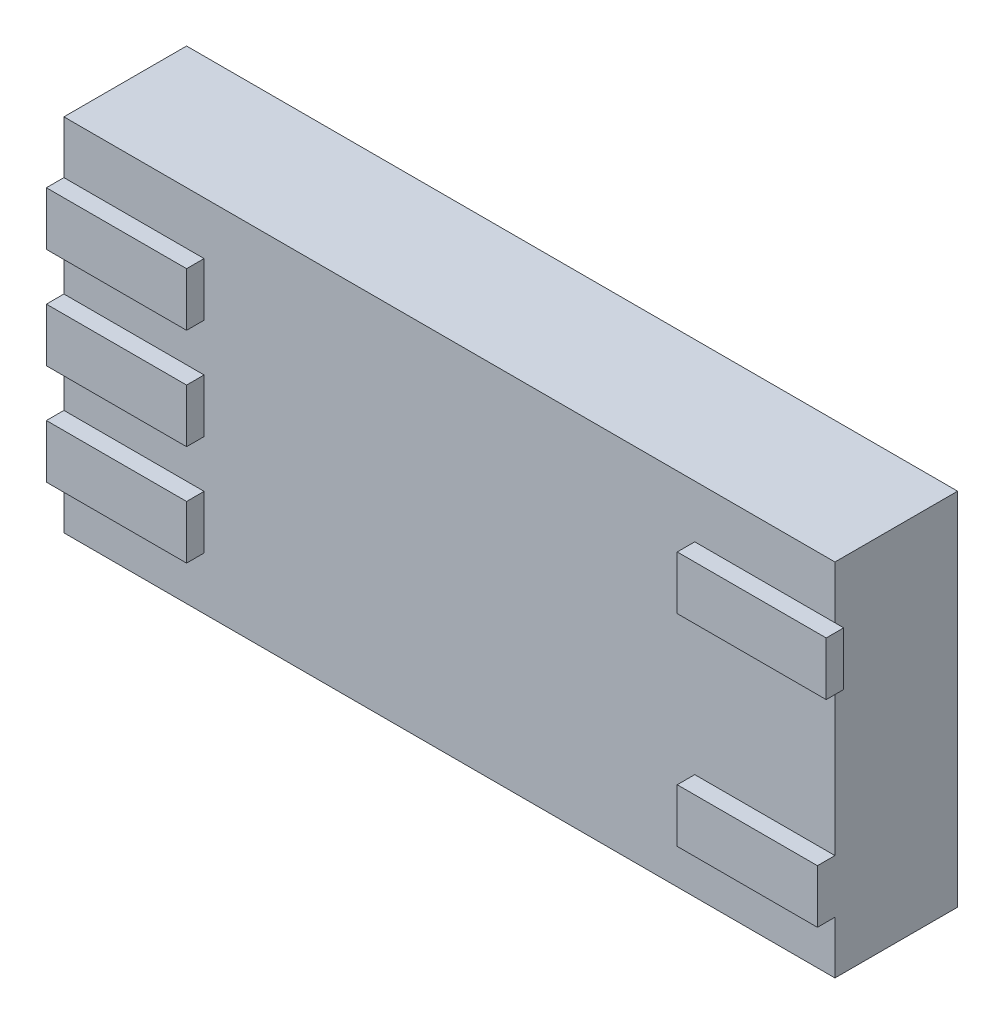
SolidWorks part; units mm, degrees
ref_plane "Front Plane" through (0, 0, 0) normal (0, 0, 1) x (1, 0, 0)
ref_plane "Top Plane" through (0, 0, 0) normal (0, 1, 0) x (1, 0, 0)
ref_plane "Right Plane" through (0, 0, 0) normal (1, 0, 0) x (0, 0, -1)
sketch "Sketch1" plane through (0, 0, 0) normal (0, 0, 1) x (1, 0, 0)
  line L1 (0, 26.1112) -> (55.88, 26.1112)
  line L2 (0, 26.1112) -> (0, 0)
  line L3 (0, 0) -> (55.88, 0)
  line L4 (55.88, 26.1112) -> (55.88, 0)
  dimension "D1" = 55.88
  dimension "D2" = 26.1112
extrude "Boss-Extrude1" add sketch "Sketch1" along normal blind 8.89
sketch "Sketch2" plane through (0, 0, 8.89) normal (0, 0, 1) x (1, 0, 0)
  line L0 (0, 7.6852) -> (10.16, 7.6852)
  line L1 (0, 14.9905) -> (10.16, 14.9905)
  line L2 (0, 14.9905) -> (0, 11.1207)
  line L3 (0, 11.1207) -> (10.16, 11.1207)
  line L4 (10.16, 14.9905) -> (10.16, 11.1207)
  line L5 (0, 7.6852) -> (0, 3.8153)
  line L6 (0, 3.8153) -> (10.16, 3.8153)
  line L7 (10.16, 7.6852) -> (10.16, 3.8153)
  line L8 (0, 22.2959) -> (10.16, 22.2959)
  line L9 (0, 22.2959) -> (0, 18.426)
  line L10 (0, 18.426) -> (10.16, 18.426)
  line L11 (10.16, 22.2959) -> (10.16, 18.426)
  line L12 (45.72, 7.6852) -> (55.88, 7.6852)
  line L13 (45.72, 7.6852) -> (45.72, 3.8153)
  line L14 (45.72, 3.8153) -> (55.88, 3.8153)
  line L15 (55.88, 7.6852) -> (55.88, 3.8153)
  line L16 (55.88, 0) -> (55.88, 26.1112) construction
  line L17 (45.72, 22.2959) -> (55.88, 22.2959)
  line L18 (45.72, 22.2959) -> (45.72, 18.426)
  line L19 (45.72, 18.426) -> (55.88, 18.426)
  line L20 (55.88, 22.2959) -> (55.88, 18.426)
  line L21 (5.08, 26.1112) -> (5.08, 22.2959) construction
  line L22 (5.08, 18.426) -> (5.08, 14.9905) construction
  line L23 (55.88, 26.1112) -> (0, 26.1112) construction
  line L24 (5.08, 3.8153) -> (5.08, 0) construction
  line L25 (0, 26.1112) -> (0, 0) construction
  line L26 (5.08, 11.1207) -> (5.08, 7.6852) construction
  line L27 (0, 0) -> (55.88, 0) construction
  dimension "D1" = 10.16
  dimension "D2" = 3.8153
  dimension "D3" = 3.4355
extrude "Boss-Extrude2" add sketch "Sketch2" along normal blind 1.27
sketch "Sketch3" plane through (55.88, 0, 0) normal (1, 0, 0) x (0, 0, -1)
  line L0 (-10.16, 18.426) -> (-10.16, 22.2959) construction
  line L1 (-10.16, 22.2959) -> (-8.89, 22.2959)
  line L2 (-10.16, 22.2959) -> (-10.16, 18.426)
  line L3 (-10.16, 18.426) -> (-8.89, 18.426)
  line L4 (-8.89, 22.2959) -> (-8.89, 18.426)
  line L5 (-8.89, 7.6852) -> (-8.89, 18.426) construction
extrude "Boss-Extrude3" add sketch "Sketch3" along normal blind 0.635
